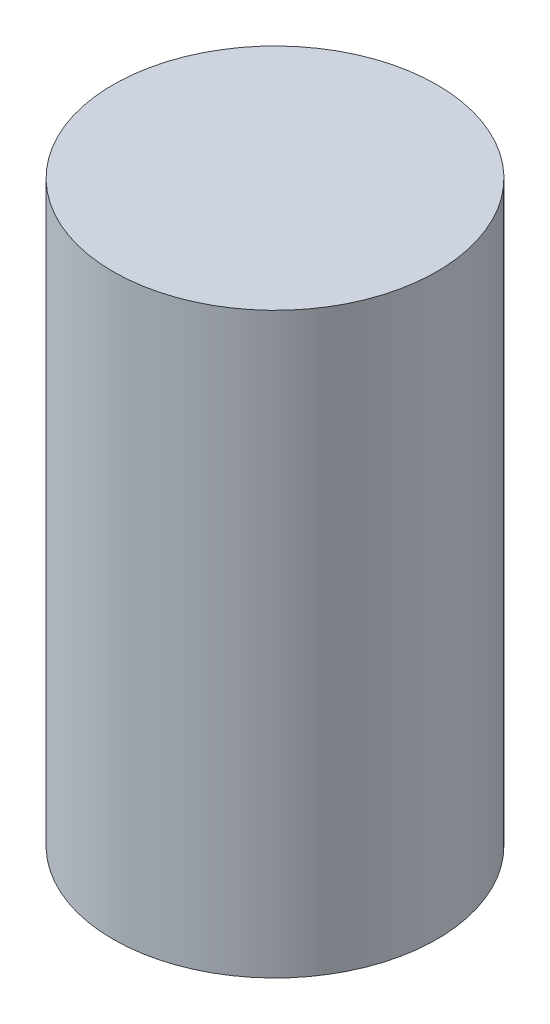
SolidWorks part; units mm, degrees
ref_plane "前视基准面" through (0, 0, 0) normal (0, 0, 1) x (1, 0, 0)
ref_plane "上视基准面" through (0, 0, 0) normal (0, 1, 0) x (1, 0, 0)
ref_plane "右视基准面" through (0, 0, 0) normal (1, 0, 0) x (0, 0, -1)
other "Configuration Table"
sketch "草图1" plane through (0, 0, 0) normal (0, 1, 0) x (1, 0, 0)
  circle A0 centre (0, 0) radius 7
extrude "凸台-拉伸1" add sketch "草图1" along normal blind 20
sketch "草图4" plane through (0, 20, 0) normal (0, 1, 0) x (1, 0, 0)
  circle A1 centre (0, 0) radius 7
  circle A2 centre (0, 0) radius 7
  dimension "D1" = 0
extrude "凸台-拉伸2" add sketch "草图4" along normal blind 5
